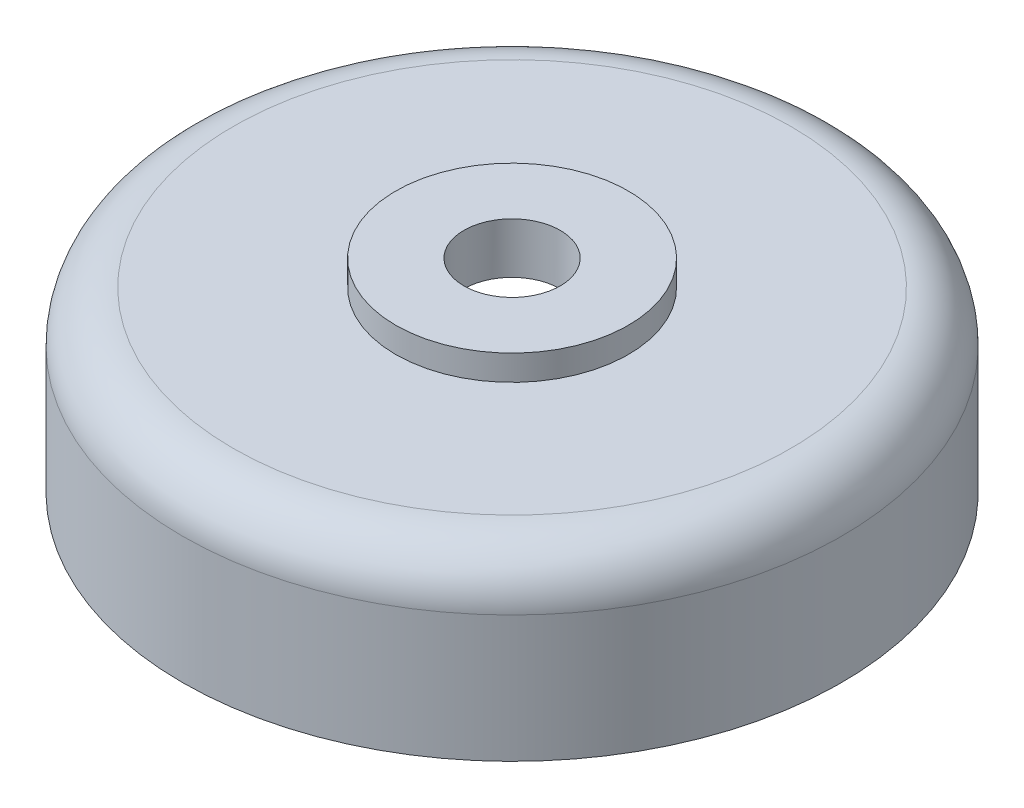
SolidWorks part; units mm, degrees
ref_plane "Front Plane" through (0, 0, 0) normal (0, 0, 1) x (1, 0, 0)
ref_plane "Top Plane" through (0, 0, 0) normal (0, 1, 0) x (1, 0, 0)
ref_plane "Right Plane" through (0, 0, 0) normal (1, 0, 0) x (0, 0, -1)
sketch "Sketch1" plane through (0, 0, 0) normal (0, 1, 0) x (1, 0, 0)
  circle A0 centre (0, 0) radius 65
extrude "Boss-Extrude1" add sketch "Sketch1" along normal blind 35
sketch "Sketch2" plane through (0, 35, 0) normal (0, 1, 0) x (1, 0, 0)
  circle A0 centre (0, 0) radius 22.945
  dimension "D1" = 45.89
extrude "Boss-Extrude2" add sketch "Sketch2" along normal blind 5
sketch "Sketch3" plane through (0, 40, 0) normal (0, 1, 0) x (1, 0, 0)
  circle A0 centre (0, 0) radius 9.5
  dimension "D1" = 19
extrude "Cut-Extrude1" cut sketch "Sketch3" against normal blind 99
sketch "Sketch4" plane through (0, 0, 0) normal (0, -1, 0) x (1, 0, 0)
  circle A0 centre (0, 0) radius 60
extrude "Cut-Extrude2" cut sketch "Sketch4" against normal blind 30
fillet "Fillet1" radius 10 1 edges at (0, 35, 65)
fillet "Fillet2" radius 10 1 edges at (0, 30, -60)
